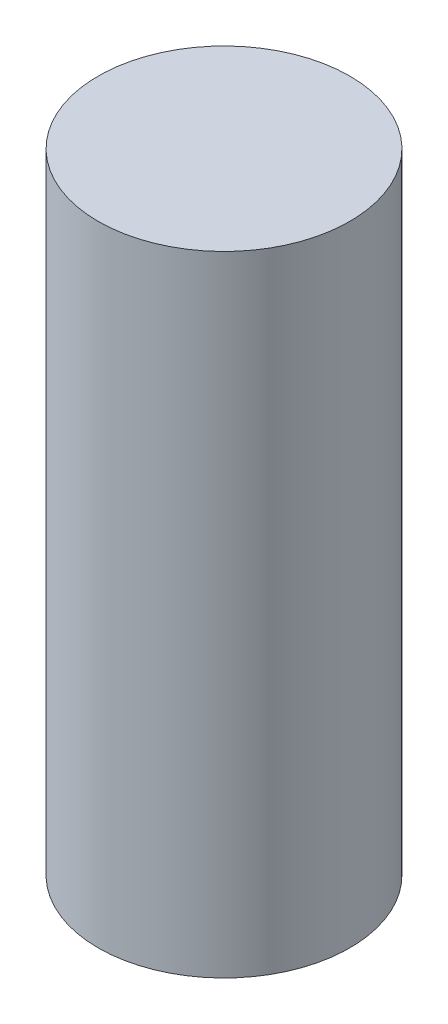
SolidWorks part; units mm, degrees
material "AISI 1020"
ref_plane "Plan de face" through (0, 0, 0) normal (0, 0, 1) x (1, 0, 0)
ref_plane "Plan de dessus" through (0, 0, 0) normal (0, 1, 0) x (1, 0, 0)
ref_plane "Plan de droite" through (0, 0, 0) normal (1, 0, 0) x (0, 0, -1)
sketch "Esquisse1" plane through (0, 0, 0) normal (0, 1, 0) x (1, 0, 0)
  circle A0 centre (0, 0) radius 5
  point P3 (0, 0)
  dimension "D1" = 10
extrude "Boss.-Extru.1" add sketch "Esquisse1" along normal mid plane 25
sketch "Esquisse2" plane through (0, 12.5, 0) normal (0, 1, 0) x (1, 0, 0)
  line L0 (0, -5.5) -> (0, 5.5) construction
  line L1 (-0.0159, -0.0105) -> (-8.3163, -5.4873) construction
  line L3 (0, 5) -> (8.032, 5) construction
  line L5 (0, 0) -> (8.1811, 0) construction
  line L9 (-5.5, 0) -> (5.5, 0) construction
  line L10 (0, 5) -> (0, 25.7241) construction
  arc A0 (-4.1734, -2.7537) -> (-6.4393, -2.7451) centre (-5.2903, 1.4799) cw
  circle A1 centre (0, 0) radius 5 construction
  spline S0 degree 3 poles (0, -5) (-1.5208, -5) (-5.6434, -4.7601) (-6.4094, -3.0474) (-6.4393, -2.7451) knots 0 0 0 0 0.74454 1 1 1 1
  point P16 (0, 0)
  point P20 (0, 15.3621)
  point P22 (0, 0)
  point P23 (-6.6119, -2.2984)
  point P24 (-6.4393, -2.7537)
  dimension "D2" = 7
  dimension "D1" = 56.582
